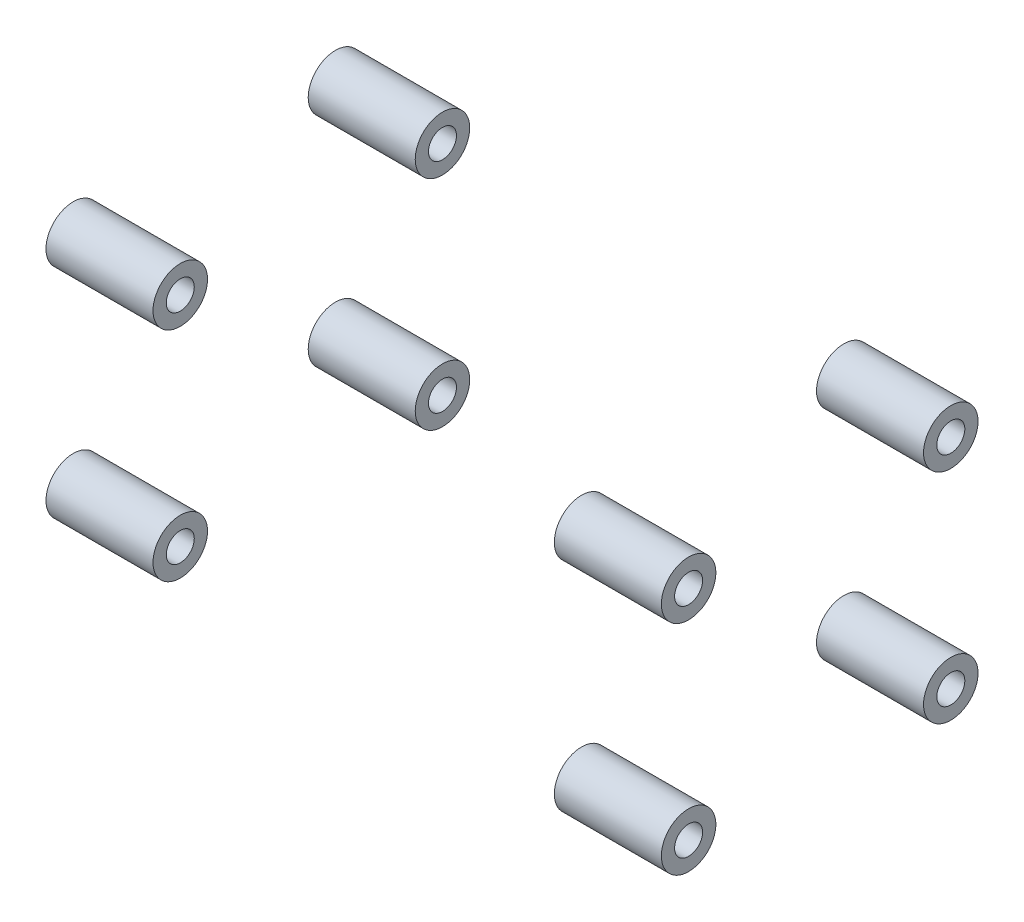
SolidWorks part; units mm, degrees
material "6061-T6 (SS)"
ref_plane "Front Plane" through (0, 0, 0) normal (0, 0, 1) x (1, 0, 0)
ref_plane "Top Plane" through (0, 0, 0) normal (0, 1, 0) x (1, 0, 0)
ref_plane "Right Plane" through (0, 0, 0) normal (1, 0, 0) x (0, 0, -1)
sketch "Sketch2" plane through (0, 0, 0) normal (1, 0, 0) x (0, 0, -1)
  circle A0 centre (-9.7272, 12.7) radius 1.632 construction
  circle A1 centre (-9.7272, -12.7) radius 1.632 construction
  circle A2 centre (-40.279, -12.7) radius 1.632 construction
  circle A3 centre (-40.279, 12.7) radius 1.632 construction
  circle A4 centre (-9.7272, 12.7) radius 1.632
  circle A5 centre (-9.7272, -12.7) radius 1.632
  circle A6 centre (-40.279, -12.7) radius 1.6319
  circle A7 centre (-40.279, 12.7) radius 1.6319
  circle A8 centre (-40.279, 12.7) radius 3.175
  circle A9 centre (-40.279, -12.7) radius 3.175
  circle A10 centre (-9.7272, -12.7) radius 3.175
  circle A11 centre (-9.7272, 12.7) radius 3.175
  dimension "D1" = 6.35
extrude "Boss-Extrude2" add sketch "Sketch2" along normal up to surface (12.47 mm away) from surface at 23.38
mirror "Mirror2" about plane through (0, 0, 0) normal (1, 0, 0) of bodies 112 109 110 111
